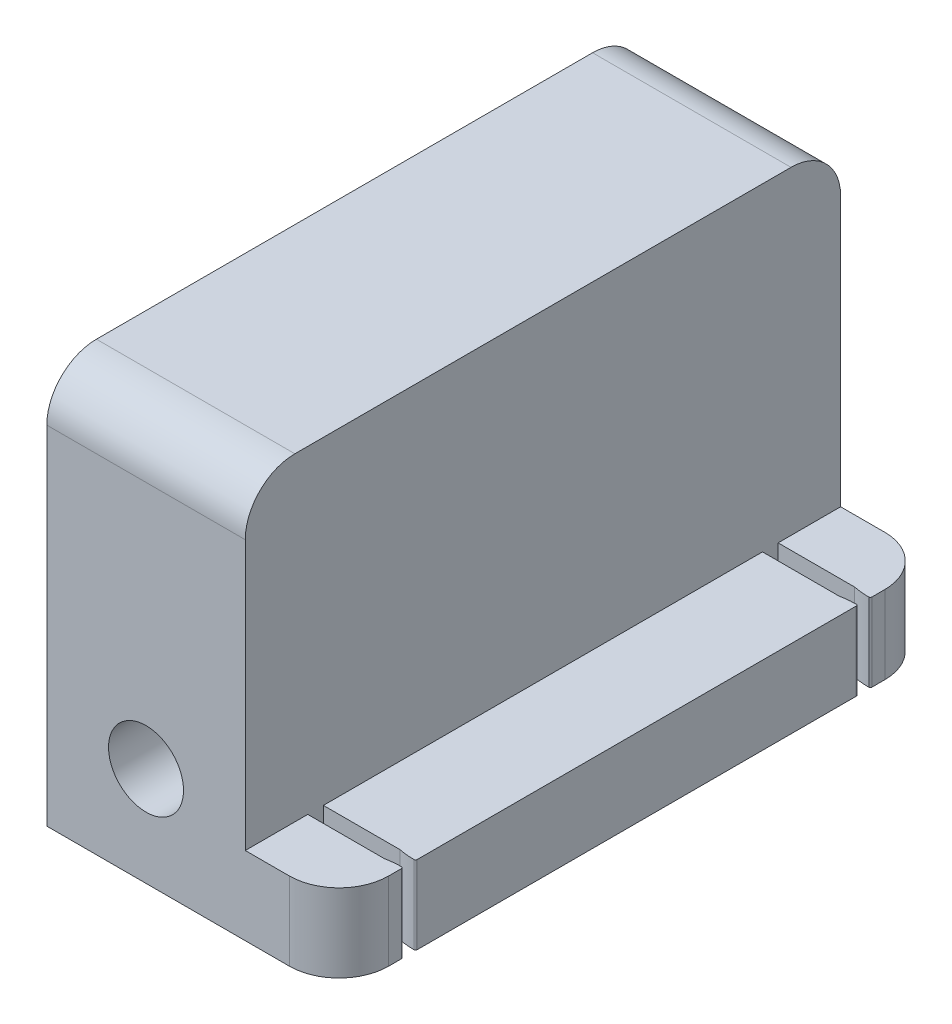
SolidWorks part; units mm, degrees
ref_plane "Front Plane" through (0, 0, 0) normal (0, 0, 1) x (1, 0, 0)
ref_plane "Top Plane" through (0, 0, 0) normal (0, 1, 0) x (1, 0, 0)
ref_plane "Right Plane" through (0, 0, 0) normal (1, 0, 0) x (0, 0, -1)
sketch "Sketch1" plane through (0, 0, 0) normal (0, 0, 1) x (1, 0, 0)
  line L0 (0, 12.7) -> (0, -12.7) construction
  line L1 (-12.7, -25.4) -> (12.7, -25.4)
  line L2 (-12.7, -25.4) -> (-12.7, 25.4)
  line L3 (-12.7, 25.4) -> (12.7, 25.4)
  line L4 (12.7, -25.4) -> (12.7, 25.4)
  line L5 (-12.7, -25.4) -> (12.7, 25.4) construction
  line L6 (-12.7, 25.4) -> (12.7, -25.4) construction
  circle A0 centre (0, -12.7) radius 4.8006
  circle A1 centre (0, 12.7) radius 4.8006 construction
  point P0 (0, 0)
  point P9 (0, 0)
  dimension "D3" = 9.6012
  dimension "D1" = 50.8
  dimension "D2" = 25.4
  dimension "D4" = 12.7
extrude "Boss-Extrude1" add sketch "Sketch1" along normal mid plane 76.2
sketch "Sketch2" plane through (0, 0, 0) normal (1, 0, 0) x (0, 0, -1)
  line L0 (0, 0) -> (0, 25.4) construction
  line L1 (-38.1, 25.4) -> (38.1, 25.4) construction
  circle A0 centre (-25.4, 12.7) radius 4.8006
  circle A1 centre (25.4, 12.7) radius 4.8006
  dimension "D2" = 25.4
  dimension "D1" = 9.6012
  dimension "D3" = 12.7
extrude "Cut-Extrude1" cut sketch "Sketch2" against normal through all
sketch "Sketch3" plane through (0, -25.4, 0) normal (0, -1, 0) x (1, 0, 0)
  line L0 (0, 0) -> (18.7, 0) construction
  line L1 (12.7, 38.1) -> (24.7, 38.1)
  line L2 (12.7, 38.1) -> (12.7, -38.1)
  line L3 (12.7, -38.1) -> (24.7, -38.1)
  line L4 (24.7, 38.1) -> (24.7, -38.1)
  line L5 (12.7, 38.1) -> (24.7, -38.1) construction
  line L6 (12.7, -38.1) -> (24.7, 38.1) construction
  point P0 (18.7, 0)
  point P8 (12.7, 38.1)
  dimension "D1" = 12
extrude "Boss-Extrude2" add sketch "Sketch3" against normal blind 10
sketch "Sketch4" plane through (0, 0, 0) normal (0, 1, 0) x (1, 0, 0)
  line L0 (18.7, 29.1) -> (12.7, 29.1) construction
  line L1 (24.7, 30.1) -> (24.7, 28.1)
  line L2 (12.7, 30.1) -> (12.7, 28.1)
  line L3 (12.7, 28.1) -> (22.5, 28.1)
  line L4 (22.5, 30.1) -> (12.7, 30.1)
  line L5 (0, 0) -> (24.7, 0) construction
  line L6 (24.7, -30.1) -> (24.7, -28.1)
  line L7 (12.7, -28.1) -> (22.5, -28.1)
  line L8 (12.7, -30.1) -> (12.7, -28.1)
  line L9 (24.7, 38.1) -> (24.7, -38.1) construction
  line L10 (12.7, 28.1) -> (24.7, 28.1) construction
  line L11 (12.7, 28.1) -> (12.7, 30.1) construction
  line L12 (12.7, 30.1) -> (24.7, 30.1) construction
  line L13 (24.7, 28.1) -> (24.7, 30.1) construction
  line L14 (12.7, 28.1) -> (24.7, 30.1) construction
  line L15 (12.7, 30.1) -> (24.7, 28.1) construction
  line L16 (12.7, -38.1) -> (12.7, 38.1) construction
  line L17 (12.7, 38.1) -> (24.7, 38.1) construction
  line L18 (22.5, -30.1) -> (12.7, -30.1)
  line L19 (22.5, 30.1) -> (24.5, 30.1) construction
  line L20 (22.5, 30.1) -> (22.5, 29.9) construction
  line L21 (22.5, 29.9) -> (24.5, 29.9) construction
  line L22 (24.5, 30.1) -> (24.5, 29.9) construction
  arc A0 (24.7, 28.1) -> (24.5, 28.3) centre (24.5, 28.1) ccw
  arc A1 (22.5, 28.1) -> (24.5, 28.3) centre (24.5, 18.2) cw
  arc A2 (22.5, -30.1) -> (24.5, -29.9) centre (24.5, -40) cw
  arc A3 (24.7, -30.1) -> (24.5, -29.9) centre (24.5, -30.1) ccw
  arc A4 (24.7, 30.1) -> (24.5, 29.9) centre (24.5, 30.1) cw
  arc A5 (22.5, 30.1) -> (24.5, 29.9) centre (24.5, 40) ccw
  arc A6 (24.7, -28.1) -> (24.5, -28.3) centre (24.5, -28.1) cw
  arc A7 (22.5, -28.1) -> (24.5, -28.3) centre (24.5, -18.2) ccw
  point P22 (18.7, 29.1)
  dimension "D6" = 10
  dimension "D7" = 2
  dimension "D8" = 0.2
  dimension "D9" = 2
extrude "Cut-Extrude2" cut sketch "Sketch4" against normal through all
fillet "Fillet1" radius 6.35 4 edges at (24.7, -20.4, -38.1) (24.7, -20.4, 38.1) (0, 25.4, -38.1) (0, 25.4, 38.1)
equation "\"D\"= 0.378"
equation "\"D3@Sketch1\"=\"D\""
equation "\"H\"=0.5"
equation "\"D4@Sketch1\"=\"H\""
equation "\"D1@Sketch2\"=\"D\""
equation "\"D3@Sketch2\"=\"H\""
